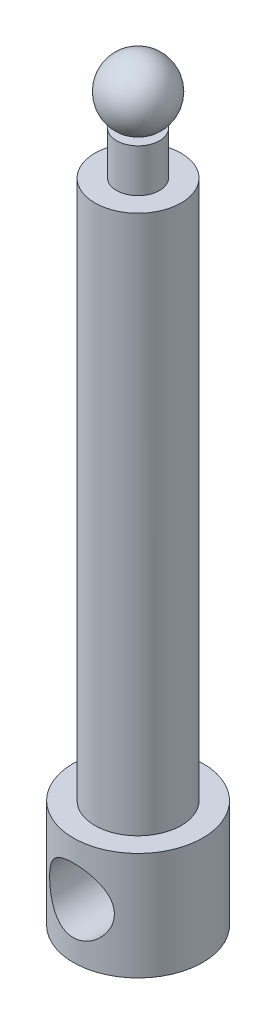
SolidWorks part; units mm, degrees
ref_plane "Płaszczyzna przednia" through (0, 0, 0) normal (0, 0, 1) x (1, 0, 0)
ref_plane "Płaszczyzna górna" through (0, 0, 0) normal (0, 1, 0) x (1, 0, 0)
ref_plane "Płaszczyzna prawa" through (0, 0, 0) normal (1, 0, 0) x (0, 0, -1)
sketch "Szkic1" plane through (0, 0, 0) normal (0, 1, 0) x (1, 0, 0)
  circle A0 centre (0, 0) radius 2
  dimension "D1" = 4
extrude "Dodanie-wyciągnięcie1" add sketch "Szkic1" along normal blind 25
sketch "Szkic2" plane through (0, 25, 0) normal (0, 1, 0) x (1, 0, 0)
  circle A0 centre (0, 0) radius 1
  dimension "D1" = 2
extrude "Dodanie-wyciągnięcie2" add sketch "Szkic2" along normal blind 2
sketch "Szkic3" plane through (0, 0, 0) normal (0, 0, 1) x (1, 0, 0)
  line L0 (0, 0) -> (0, 29.9738)
  line L1 (0, 29.9738) -> (0, 26.9738)
  line L2 (0, 0) -> (0, 26.9738)
  arc A0 (0, 26.9738) -> (0, 29.9738) centre (0, 28.4738) ccw
  dimension "D1" = 3
revolve "Obrót3" add sketch "Szkic3" angle 360 about L0
sketch "Szkic4" plane through (0, 0, 0) normal (0, -1, 0) x (1, 0, 0)
  circle A0 centre (0, 0) radius 3
  dimension "D1" = 6
extrude "Dodanie-wyciągnięcie3" add sketch "Szkic4" along normal blind 5
sketch "Szkic5" plane through (0, 0, 0) normal (0, 0, 1) x (1, 0, 0)
  circle A0 centre (0, -2.5) radius 1.5
  dimension "D2" = 3
extrude "Wytnij-wyciągnięcie1" cut sketch "Szkic5" against normal through all both and the other way through all
